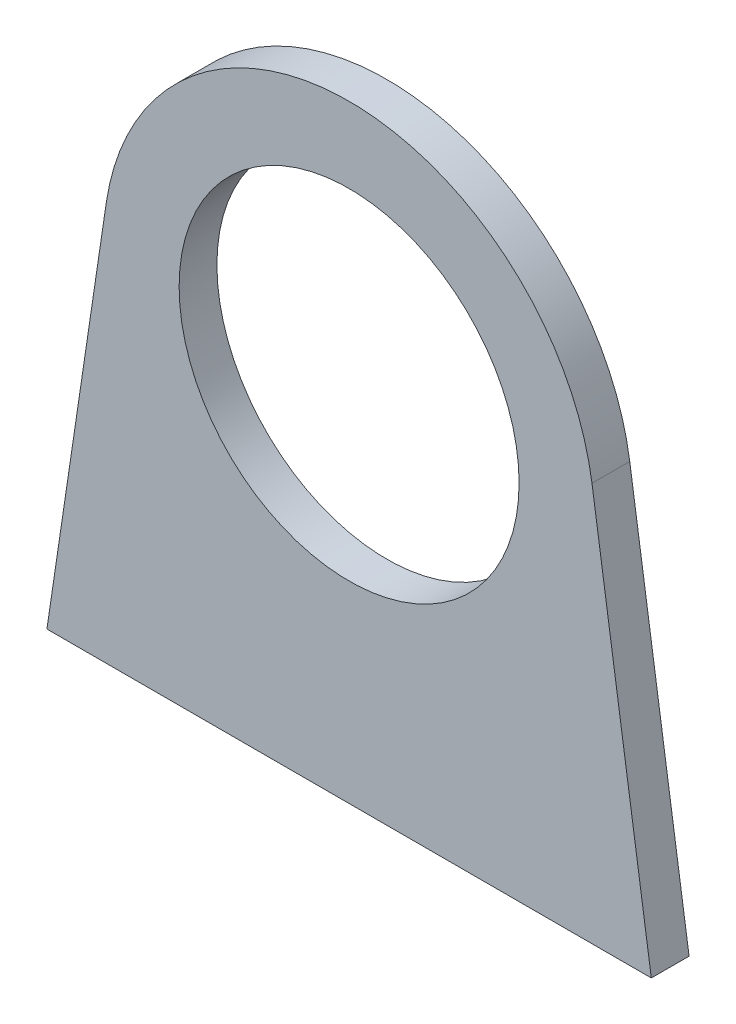
SolidWorks part; units mm, degrees
ref_plane "Front Plane" through (0, 0, 0) normal (0, 0, 1) x (1, 0, 0)
ref_plane "Top Plane" through (0, 0, 0) normal (0, 1, 0) x (1, 0, 0)
ref_plane "Right Plane" through (0, 0, 0) normal (1, 0, 0) x (0, 0, -1)
sketch "Sketch1" plane through (0, 0, 0) normal (0, 0, 1) x (1, 0, 0)
  line L0 (-25.4, -30.48) -> (25.4, -30.48)
  line L2 (-25.4, -30.48) -> (-20.4128, 3.0373)
  line L3 (20.4128, 3.0373) -> (25.4, -30.48)
  circle A0 centre (0, 0) radius 14.2875
  circle A1 centre (0, 0) radius 20.6375 construction
  arc A2 (-20.4128, 3.0373) -> (20.4128, 3.0373) centre (0, 0) cw
  point P5 (-26.4, -30.48)
  point P6 (0, -30.48)
  dimension "D1" = 28.575
  dimension "D2" = 30.48
  dimension "D4" = 50.8
  dimension "D3" = 6.35
extrude "Boss-Extrude1" add sketch "Sketch1" along normal blind 3.175
